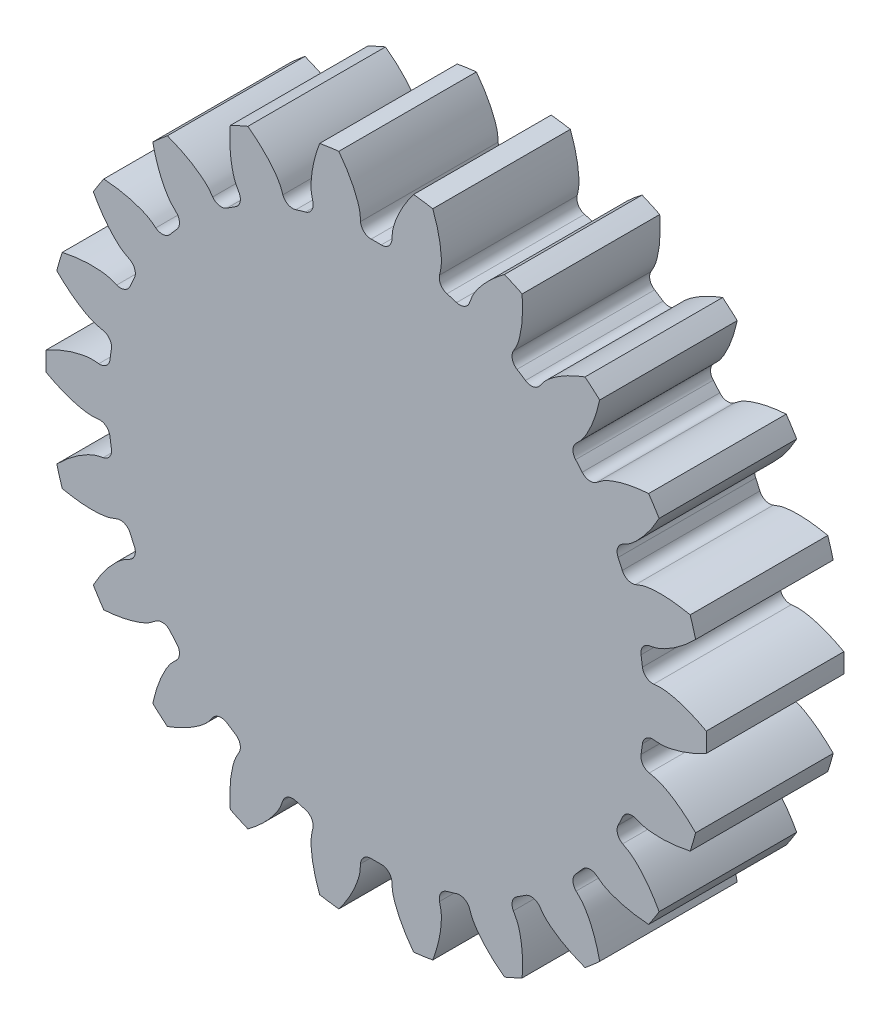
SolidWorks part; units mm, degrees
ref_plane "前视基准面" through (0, 0, 0) normal (0, 0, 1) x (1, 0, 0)
ref_plane "上视基准面" through (0, 0, 0) normal (0, 1, 0) x (1, 0, 0)
ref_plane "右视基准面" through (0, 0, 0) normal (1, 0, 0) x (0, 0, -1)
other "Configuration Table"
ref_axis "Axis1" through (0, 0, -88.99) along (0, 0, 1)
sketch "草图1" plane through (0, 0, 0) normal (0, 0, 1) x (1, 0, 0)
  circle A0 centre (0, 0) radius 12
extrude "LaShenA" add sketch "草图1" along normal blind 5
sketch "SketchA" plane through (0, 0, 5) normal (0, 0, 1) x (1, 0, 0)
  line L0 (0, 0) -> (0, 12) construction
  arc A0 (0.1829, 9.7483) -> (-0.1829, 9.7483) centre (0, 0) ccw
  arc A1 (1.7922, 12.4394) -> (-1.7922, 12.4394) centre (0, 0) ccw
  arc A2 (-0.1829, 9.7483) -> (-0.5693, 10.1058) centre (-0.19, 10.1282) cw
  arc A3 (0.5693, 10.1058) -> (0.1829, 9.7483) centre (0.19, 10.1282) cw
  circle A4 centre (0, 0) radius 10.3366 construction
  circle A5 centre (0, 0) radius 12 construction
  circle A6 centre (0, 0) radius 9.75 construction
  circle A7 centre (0, 0) radius 11 construction
  spline S0 degree 3 poles (0.5693, 10.1058) (0.5736, 10.1777) (0.5776, 10.2793) (0.5937, 10.3939) (0.606, 10.4523) (0.6168, 10.4986) (0.6308, 10.5517) (0.6482, 10.6114) (0.6693, 10.6775) (0.6947, 10.75) (0.7246, 10.8287) (0.7593, 10.9132) (0.7992, 11.0036) (0.8447, 11.0994) (0.8959, 11.2005) (0.9533, 11.3067) (1.0172, 11.4176) (1.0878, 11.533) (1.1655, 11.6527) (1.2504, 11.7762) (1.3429, 11.9034) (1.4432, 12.0339) (1.5907, 12.2156) (1.7093, 12.3501) (1.7922, 12.4394) knots 0.122554 0.122554 0.122554 0.122554 0.192705 0.222547 0.235684 0.251209 0.269123 0.289425 0.312116 0.337195 0.364662 0.394518 0.426763 0.461396 0.498418 0.537828 0.579626 0.623813 0.670389 0.719353 0.770705 0.824446 0.880576 1 1 1 1
  spline S1 degree 3 poles (-0.5693, 10.1058) (-0.5736, 10.1777) (-0.5776, 10.2793) (-0.5937, 10.3939) (-0.606, 10.4523) (-0.6168, 10.4986) (-0.6308, 10.5517) (-0.6482, 10.6114) (-0.6693, 10.6775) (-0.6947, 10.75) (-0.7246, 10.8287) (-0.7593, 10.9132) (-0.7992, 11.0036) (-0.8447, 11.0994) (-0.8959, 11.2005) (-0.9533, 11.3067) (-1.0172, 11.4176) (-1.0878, 11.533) (-1.1655, 11.6527) (-1.2504, 11.7762) (-1.3429, 11.9034) (-1.4432, 12.0339) (-1.5907, 12.2156) (-1.7093, 12.3501) (-1.7922, 12.4394) knots 0.122554 0.122554 0.122554 0.122554 0.192705 0.222547 0.235684 0.251209 0.269123 0.289425 0.312116 0.337195 0.364662 0.394518 0.426763 0.461396 0.498418 0.537828 0.579626 0.623813 0.670389 0.719353 0.770705 0.824446 0.880576 1 1 1 1
  dimension "D1" = 0.38
  dimension "Db" = 20.6732
  dimension "Da" = 24
  dimension "Df" = 19.5
  dimension "Dn" = 22
extrude "Cut-ExtrudeA" cut sketch "SketchA" against normal blind 10
pattern_circular "www.KYTool.cn" count 22 over 360 about axis through (0, 0, -88.99) along (0, 0, 1) of "Cut-ExtrudeA"
